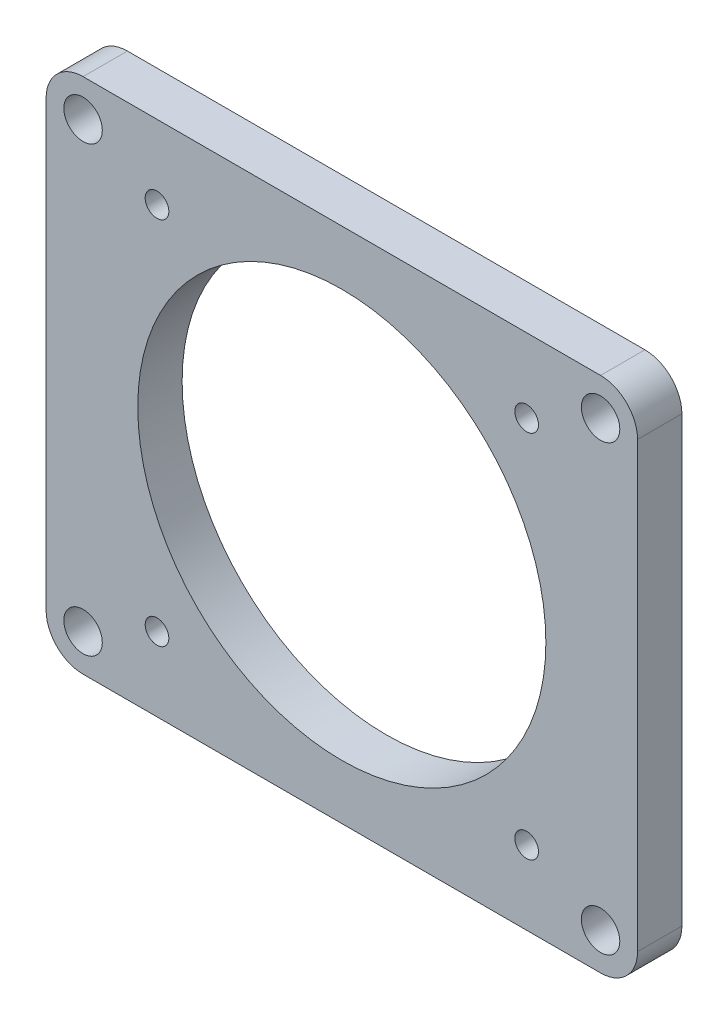
SolidWorks part; units mm, degrees
ref_plane "Front Plane" through (0, 0, 0) normal (0, 0, 1) x (1, 0, 0)
ref_plane "Top Plane" through (0, 0, 0) normal (0, 1, 0) x (1, 0, 0)
ref_plane "Right Plane" through (0, 0, 0) normal (1, 0, 0) x (0, 0, -1)
sketch "Sketch1" plane through (0, 0, 0) normal (0, 0, 1) x (1, 0, 0)
  line L1 (-35, 35) -> (35, 35)
  line L2 (-40, 30) -> (-40, -30)
  line L3 (-35, -35) -> (35, -35)
  line L4 (40, 30) -> (40, -30)
  circle A0 centre (0, 0) radius 27.6
  circle A1 centre (-35, 30) radius 2.6
  circle A2 centre (-35, -30) radius 2.6
  circle A3 centre (35, -30) radius 2.6
  circle A4 centre (35, 30) radius 2.6
  arc A5 (-40, -30) -> (-35, -35) centre (-35, -30) ccw
  arc A6 (35, -35) -> (40, -30) centre (35, -30) ccw
  arc A7 (40, 30) -> (35, 35) centre (35, 30) ccw
  arc A8 (-35, 35) -> (-40, 30) centre (-35, 30) ccw
  point P21 (-40, -35)
  point P26 (40, 35)
  point P29 (-40, 35)
  dimension "D1" = 55.2
  dimension "D10" = 5.2
  dimension "D11" = 5.2
  dimension "D12" = 5.2
  dimension "D13" = 5.2
  dimension "D14" = 5
  dimension "D2" = 70
  dimension "D3" = 80
  dimension "D4" = 40
  dimension "D5" = 35
  dimension "D6" = 70
  dimension "D7" = 60
  dimension "D8" = 30
  dimension "D9" = 35
extrude "Boss-Extrude1" add sketch "Sketch1" along normal blind 6
sketch "Sketch4" plane through (0, 0, 0) normal (0, 0, -1) x (-1, 0, 0)
  line L0 (-25, 25) -> (-25, -25) construction
  line L1 (-25, -25) -> (25, -25) construction
  line L2 (25, -25) -> (25, 25) construction
  line L3 (25, 25) -> (-25, 25) construction
  circle A0 centre (-25, 25) radius 1.6
  circle A1 centre (25, 25) radius 1.6
  circle A2 centre (-25, -25) radius 1.6
  circle A3 centre (25, -25) radius 1.6
  dimension "D4" = 3.2
  dimension "D5" = 3.2
  dimension "D6" = 3.2
  dimension "D7" = 3.2
  dimension "D1" = 50
  dimension "D2" = 25
  dimension "D3" = 25
extrude "Cut-Extrude2" cut sketch "Sketch4" against normal through all
sketch "Sketch5" plane through (0, 0, 0) normal (0, 0, -1) x (-1, 0, 0)
  line L1 (-28.2909, 25) -> (-26.6454, 22.15)
  line L2 (-26.6454, 22.15) -> (-23.3546, 22.15)
  line L3 (-23.3546, 22.15) -> (-21.7091, 25)
  line L4 (-21.7091, 25) -> (-23.3546, 27.85)
  line L5 (-23.3546, 27.85) -> (-26.6454, 27.85)
  line L6 (-26.6454, 27.85) -> (-28.2909, 25)
  line L7 (21.7091, 25) -> (23.3546, 22.15)
  line L8 (23.3546, 22.15) -> (26.6454, 22.15)
  line L9 (26.6454, 22.15) -> (28.2909, 25)
  line L10 (28.2909, 25) -> (26.6454, 27.85)
  line L11 (26.6454, 27.85) -> (23.3546, 27.85)
  line L12 (23.3546, 27.85) -> (21.7091, 25)
  line L13 (-28.2909, -24.9904) -> (-26.6537, -27.8452)
  line L14 (-26.6537, -27.8452) -> (-23.3629, -27.8548)
  line L15 (-23.3629, -27.8548) -> (-21.7091, -25.0096)
  line L16 (-21.7091, -25.0096) -> (-23.3463, -22.1548)
  line L17 (-23.3463, -22.1548) -> (-26.6371, -22.1452)
  line L18 (-26.6371, -22.1452) -> (-28.2909, -24.9904)
  line L19 (28.2908, -24.9751) -> (26.6238, -22.1376)
  line L20 (26.6238, -22.1376) -> (23.333, -22.1626)
  line L21 (23.333, -22.1626) -> (21.7092, -25.0249)
  line L22 (21.7092, -25.0249) -> (23.3762, -27.8624)
  line L23 (23.3762, -27.8624) -> (26.667, -27.8374)
  line L24 (26.667, -27.8374) -> (28.2908, -24.9751)
  circle A0 centre (-25, 25) radius 2.85 construction
  circle A1 centre (25, 25) radius 2.85 construction
  circle A2 centre (-25, -25) radius 2.85 construction
  circle A3 centre (25, -25) radius 2.85 construction
  dimension "D1" = 5.7
extrude "Cut-Extrude3" cut sketch "Sketch5" against normal blind 2.5
